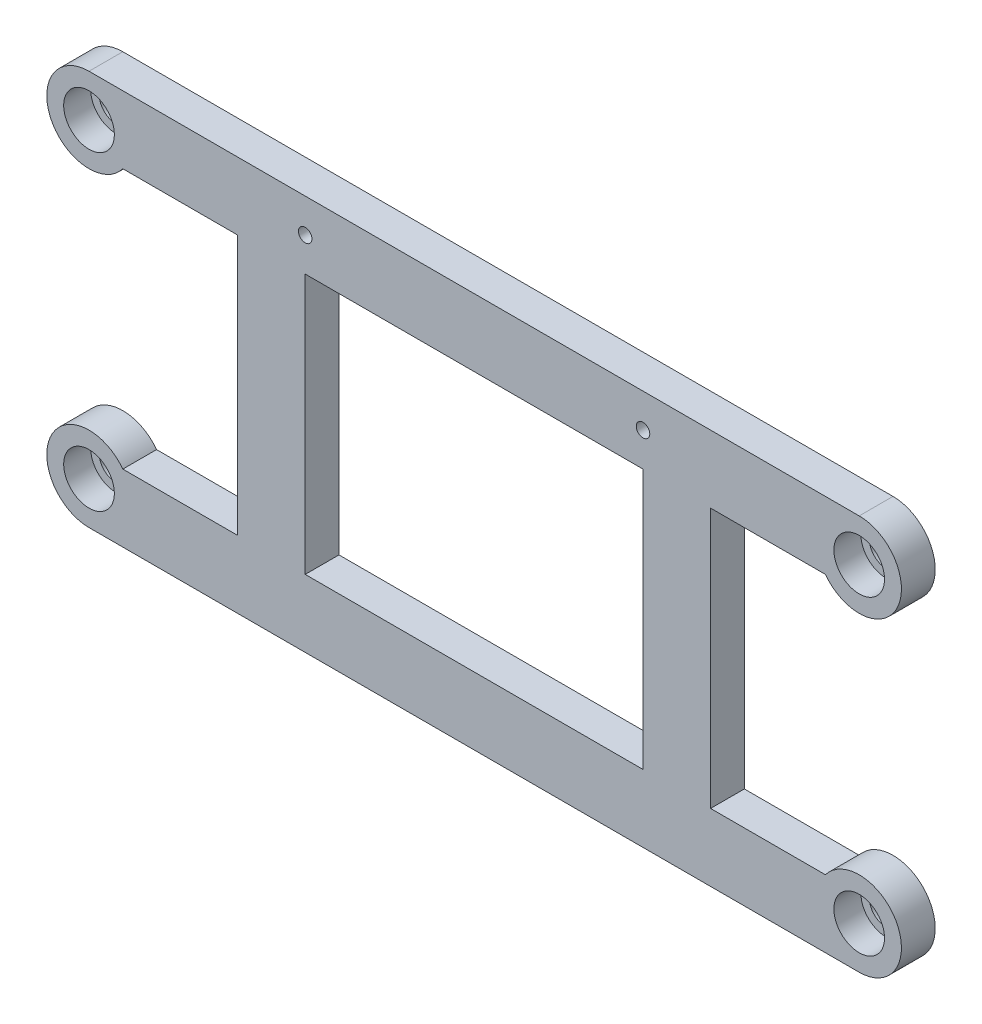
SolidWorks part; units mm, degrees
ref_plane "前视基准面" through (0, 0, 0) normal (0, 0, 1) x (1, 0, 0)
ref_plane "上视基准面" through (0, 0, 0) normal (0, 1, 0) x (1, 0, 0)
ref_plane "右视基准面" through (0, 0, 0) normal (1, 0, 0) x (0, 0, -1)
sketch "草图1" plane through (0, 0, 0) normal (0, 0, 1) x (1, 0, 0)
  line L0 (-104, 84.5) -> (-70, 84.5)
  line L1 (-70, 84.5) -> (-70, 7.5)
  line L2 (-104, 7.5) -> (-70, 7.5)
  line L3 (-114, 104.5) -> (-64, 104.5)
  line L7 (114, -12.5) -> (-114, -12.5)
  line L8 (0, 151.6854) -> (0, -40.7139) construction
  line L9 (-64, 104.5) -> (64, 104.5)
  line L10 (-50, 84.5) -> (50, 84.5)
  line L11 (-50, 84.5) -> (-50, 7.5)
  line L12 (-50, 7.5) -> (50, 7.5)
  line L16 (50, 84.5) -> (50, 7.5)
  line L23 (114, 104.5) -> (64, 104.5)
  line L24 (104, 7.5) -> (70, 7.5)
  line L25 (70, 84.5) -> (70, 7.5)
  line L26 (104, 84.5) -> (70, 84.5)
  circle A0 centre (-114, 0) radius 5
  circle A1 centre (-114, 92) radius 5
  arc A2 (-114, 104.5) -> (-104, 84.5) centre (-114, 92) ccw
  arc A3 (-104, 7.5) -> (-114, -12.5) centre (-114, 0) ccw
  arc A8 (104, 7.5) -> (114, -12.5) centre (114, 0) cw
  arc A9 (114, 104.5) -> (104, 84.5) centre (114, 92) cw
  circle A10 centre (114, 92) radius 5
  circle A11 centre (114, 0) radius 5
  point P5 (0, -12.5)
  point P12 (-104.693, 83.6556)
  point P13 (0, 0)
  point P14 (-104.693, 8.2969)
  point P19 (-213.8258, 142.6452)
  point P31 (0, 83.8883)
  point P32 (0, 103.8883)
  point P37 (0, 7.5)
  point P38 (0, 84.5)
  point P39 (0, 104.5)
  dimension "D1" = 10
  dimension "D3" = 25
  dimension "D2" = 92
  dimension "D4" = 50
  dimension "D5" = 20
  dimension "D6" = 70
  dimension "D7" = 20
  dimension "D8" = 228
  dimension "D9" = 20
extrude "凸台-拉伸1" add sketch "草图1" along normal blind 10
sketch "草图3" plane through (0, 0, 10) normal (0, 0, 1) x (1, 0, 0)
  line L0 (0, 111.1634) -> (0, -18.3618) construction
  circle A0 centre (-114, 92) radius 7.5
  circle A1 centre (-114, 0) radius 7.5
  circle A2 centre (-114, 0) radius 5 construction
  circle A3 centre (114, 0) radius 7.5
  circle A4 centre (114, 92) radius 7.5
  dimension "D1" = 15
extrude "切除-拉伸1" cut sketch "草图3" against normal offset from surface (8 mm away) 2 up to face at (109, 92, 0)
sketch "草图5" plane through (0, 0, 0) normal (0, 0, 1) x (1, 0, 0)
  line L0 (0, -12.5) -> (0, 104.5) construction
  line L1 (-114, -12.5) -> (114, -12.5) construction
  line L2 (114, 104.5) -> (-114, 104.5) construction
  circle A0 centre (-50, 94.5) radius 2
  circle A1 centre (50, 94.5) radius 2
  point P8 (0, 0)
  dimension "D1" = 4
  dimension "D2" = 10
  dimension "D3" = 100
extrude "切除-拉伸2" cut sketch "草图5" along normal up to next
